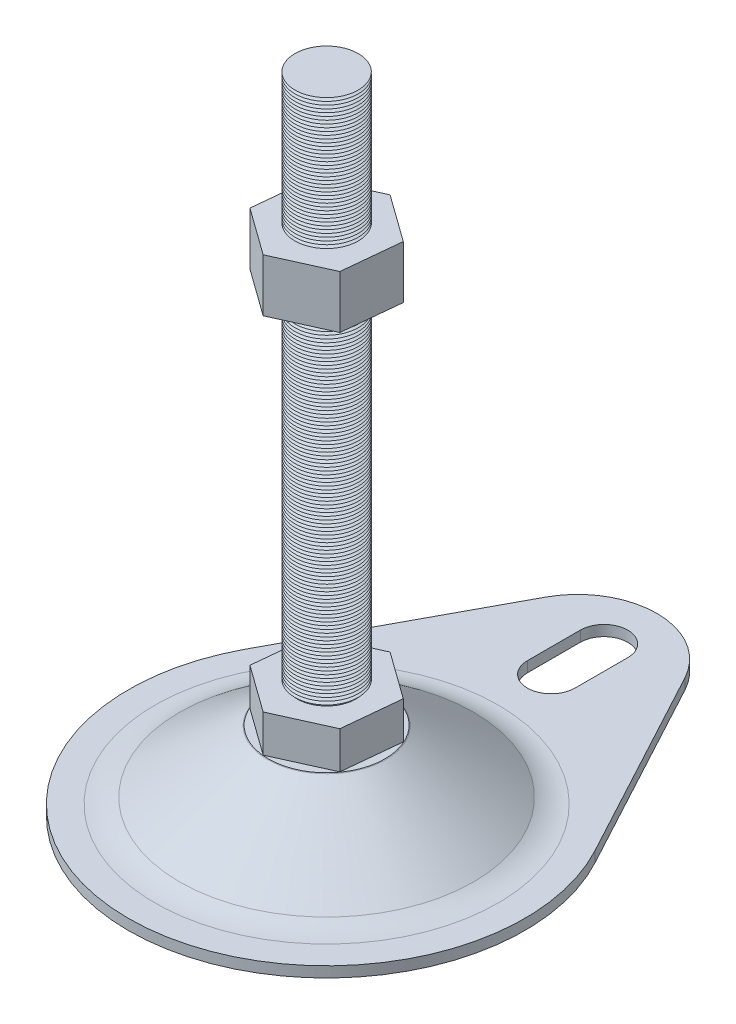
SolidWorks part; units mm, degrees
ref_plane "前视基准面" through (0, 0, 0) normal (0, 0, 1) x (1, 0, 0)
ref_plane "上视基准面" through (0, 0, 0) normal (0, 1, 0) x (1, 0, 0)
ref_plane "右视基准面" through (0, 0, 0) normal (1, 0, 0) x (0, 0, -1)
sketch "草图1" plane through (0, 0, 0) normal (0, 0, 1) x (1, 0, 0)
  line B0 (37.5, -12) -> (37.5, -14)
  line B1 (37.5, -12) -> (32.4605, -12)
  line B2 (27.8204, -10.8583) -> (11.1796, 0.8583)
  line B3 (11.1796, 0.8583) -> (11, 0.9501)
  line B4 (26.8924, -12.63) -> (10.2516, -0.9133)
  line B5 (6.5395, 0) -> (0, 0)
  line B6 (32.4605, -14) -> (37.5, -14)
  line B7 (0, 0) -> (0, 108)
  line B8 (11, 0.9501) -> (11, 8)
  line B9 (5.5767, 8) -> (11, 8)
  line B10 (5.9868, 108) -> (0, 108)
  line B11 (11, 72.9263) -> (11, 82.9263)
  line B12 (5.2185, 82.9263) -> (11, 82.9263)
  line B13 (11, 72.9263) -> (5.5349, 72.9263)
  line B14 (5.5767, 8) -> (5.1, 8.1637)
  line B15 (6, 8.4728) -> (5.1, 8.1637)
  line B16 (6, 8.4728) -> (5.1, 8.7819)
  line B17 (6, 9.091) -> (5.1, 8.7819)
  line B18 (6, 9.091) -> (5.1, 9.4002)
  line B19 (6, 9.7093) -> (5.1, 9.4002)
  line B20 (6, 9.7093) -> (5.1, 10.0184)
  line B21 (6, 10.3275) -> (5.1, 10.0184)
  line B22 (6, 10.3275) -> (5.1, 10.6366)
  line B23 (6, 10.9457) -> (5.1, 10.6366)
  line B24 (6, 10.9457) -> (5.1, 11.2548)
  line B25 (6, 11.5639) -> (5.1, 11.2548)
  line B26 (6, 11.5639) -> (5.1, 11.873)
  line B27 (6, 12.1821) -> (5.1, 11.873)
  line B28 (6, 12.1821) -> (5.1, 12.4912)
  line B29 (6, 12.8003) -> (5.1, 12.4912)
  line B30 (6, 12.8003) -> (5.1, 13.1094)
  line B31 (6, 13.4185) -> (5.1, 13.1094)
  line B32 (6, 13.4185) -> (5.1, 13.7276)
  line B33 (6, 14.0367) -> (5.1, 13.7276)
  line B34 (6, 14.0367) -> (5.1, 14.3458)
  line B35 (6, 14.6549) -> (5.1, 14.3458)
  line B36 (6, 14.6549) -> (5.1, 14.964)
  line B37 (6, 15.2731) -> (5.1, 14.964)
  line B38 (6, 15.2731) -> (5.1, 15.5822)
  line B39 (6, 15.8913) -> (5.1, 15.5822)
  line B40 (6, 15.8913) -> (5.1, 16.2005)
  line B41 (6, 16.5096) -> (5.1, 16.2005)
  line B42 (6, 16.5096) -> (5.1, 16.8187)
  line B43 (6, 17.1278) -> (5.1, 16.8187)
  line B44 (6, 17.1278) -> (5.1, 17.4369)
  line B45 (6, 17.746) -> (5.1, 17.4369)
  line B46 (6, 17.746) -> (5.1, 18.0551)
  line B47 (6, 18.3642) -> (5.1, 18.0551)
  line B48 (6, 18.3642) -> (5.1, 18.6733)
  line B49 (6, 18.9824) -> (5.1, 18.6733)
  line B50 (6, 18.9824) -> (5.1, 19.2915)
  line B51 (6, 19.6006) -> (5.1, 19.2915)
  line B52 (6, 19.6006) -> (5.1, 19.9097)
  line B53 (6, 20.2188) -> (5.1, 19.9097)
  line B54 (6, 20.2188) -> (5.1, 20.5279)
  line B55 (6, 20.837) -> (5.1, 20.5279)
  line B56 (6, 20.837) -> (5.1, 21.1461)
  line B57 (6, 21.4552) -> (5.1, 21.1461)
  line B58 (6, 21.4552) -> (5.1, 21.7643)
  line B59 (6, 22.0734) -> (5.1, 21.7643)
  line B60 (6, 22.0734) -> (5.1, 22.3825)
  line B61 (6, 22.6916) -> (5.1, 22.3825)
  line B62 (6, 22.6916) -> (5.1, 23.0008)
  line B63 (6, 23.3099) -> (5.1, 23.0008)
  line B64 (6, 23.3099) -> (5.1, 23.619)
  line B65 (6, 23.9281) -> (5.1, 23.619)
  line B66 (6, 23.9281) -> (5.1, 24.2372)
  line B67 (6, 24.5463) -> (5.1, 24.2372)
  line B68 (6, 24.5463) -> (5.1, 24.8554)
  line B69 (6, 25.1645) -> (5.1, 24.8554)
  line B70 (6, 25.1645) -> (5.1, 25.4736)
  line B71 (6, 25.7827) -> (5.1, 25.4736)
  line B72 (6, 25.7827) -> (5.1, 26.0918)
  line B73 (6, 26.4009) -> (5.1, 26.0918)
  line B74 (6, 26.4009) -> (5.1, 26.71)
  line B75 (6, 27.0191) -> (5.1, 26.71)
  line B76 (6, 27.0191) -> (5.1, 27.3282)
  line B77 (6, 27.6373) -> (5.1, 27.3282)
  line B78 (6, 27.6373) -> (5.1, 27.9464)
  line B79 (6, 28.2555) -> (5.1, 27.9464)
  line B80 (6, 28.2555) -> (5.1, 28.5646)
  line B81 (6, 28.8737) -> (5.1, 28.5646)
  line B82 (6, 28.8737) -> (5.1, 29.1828)
  line B83 (6, 29.492) -> (5.1, 29.1828)
  line B84 (6, 29.492) -> (5.1, 29.8011)
  line B85 (6, 30.1102) -> (5.1, 29.8011)
  line B86 (6, 30.1102) -> (5.1, 30.4193)
  line B87 (6, 30.7284) -> (5.1, 30.4193)
  line B88 (6, 30.7284) -> (5.1, 31.0375)
  line B89 (6, 31.3466) -> (5.1, 31.0375)
  line B90 (6, 31.3466) -> (5.1, 31.6557)
  line B91 (6, 31.9648) -> (5.1, 31.6557)
  line B92 (6, 31.9648) -> (5.1, 32.2739)
  line B93 (6, 32.583) -> (5.1, 32.2739)
  line B94 (6, 32.583) -> (5.1, 32.8921)
  line B95 (6, 33.2012) -> (5.1, 32.8921)
  line B96 (6, 33.2012) -> (5.1, 33.5103)
  line B97 (6, 33.8194) -> (5.1, 33.5103)
  line B98 (6, 33.8194) -> (5.1, 34.1285)
  line B99 (6, 34.4376) -> (5.1, 34.1285)
  line B100 (6, 34.4376) -> (5.1, 34.7467)
  line B101 (6, 35.0558) -> (5.1, 34.7467)
  line B102 (6, 35.0558) -> (5.1, 35.3649)
  line B103 (6, 35.674) -> (5.1, 35.3649)
  line B104 (6, 35.674) -> (5.1, 35.9831)
  line B105 (6, 36.2923) -> (5.1, 35.9831)
  line B106 (6, 36.2923) -> (5.1, 36.6014)
  line B107 (6, 36.9105) -> (5.1, 36.6014)
  line B108 (6, 36.9105) -> (5.1, 37.2196)
  line B109 (6, 37.5287) -> (5.1, 37.2196)
  line B110 (6, 37.5287) -> (5.1, 37.8378)
  line B111 (6, 38.1469) -> (5.1, 37.8378)
  line B112 (6, 38.1469) -> (5.1, 38.456)
  line B113 (6, 38.7651) -> (5.1, 38.456)
  line B114 (6, 38.7651) -> (5.1, 39.0742)
  line B115 (6, 39.3833) -> (5.1, 39.0742)
  line B116 (6, 39.3833) -> (5.1, 39.6924)
  line B117 (6, 40.0015) -> (5.1, 39.6924)
  line B118 (6, 40.0015) -> (5.1, 40.3106)
  line B119 (6, 40.6197) -> (5.1, 40.3106)
  line B120 (6, 40.6197) -> (5.1, 40.9288)
  line B121 (6, 41.2379) -> (5.1, 40.9288)
  line B122 (6, 41.2379) -> (5.1, 41.547)
  line B123 (6, 41.8561) -> (5.1, 41.547)
  line B124 (6, 41.8561) -> (5.1, 42.1652)
  line B125 (6, 42.4743) -> (5.1, 42.1652)
  line B126 (6, 42.4743) -> (5.1, 42.7834)
  line B127 (6, 43.0926) -> (5.1, 42.7834)
  line B128 (6, 43.0926) -> (5.1, 43.4017)
  line B129 (6, 43.7108) -> (5.1, 43.4017)
  line B130 (6, 43.7108) -> (5.1, 44.0199)
  line B131 (6, 44.329) -> (5.1, 44.0199)
  line B132 (6, 44.329) -> (5.1, 44.6381)
  line B133 (6, 44.9472) -> (5.1, 44.6381)
  line B134 (6, 44.9472) -> (5.1, 45.2563)
  line B135 (6, 45.5654) -> (5.1, 45.2563)
  line B136 (6, 45.5654) -> (5.1, 45.8745)
  line B137 (6, 46.1836) -> (5.1, 45.8745)
  line B138 (6, 46.1836) -> (5.1, 46.4927)
  line B139 (6, 46.8018) -> (5.1, 46.4927)
  line B140 (6, 46.8018) -> (5.1, 47.1109)
  line B141 (6, 47.42) -> (5.1, 47.1109)
  line B142 (6, 47.42) -> (5.1, 47.7291)
  line B143 (6, 48.0382) -> (5.1, 47.7291)
  line B144 (6, 48.0382) -> (5.1, 48.3473)
  line B145 (6, 48.6564) -> (5.1, 48.3473)
  line B146 (6, 48.6564) -> (5.1, 48.9655)
  line B147 (6, 49.2746) -> (5.1, 48.9655)
  line B148 (6, 49.2746) -> (5.1, 49.5838)
  line B149 (6, 49.8929) -> (5.1, 49.5838)
  line B150 (6, 49.8929) -> (5.1, 50.202)
  line B151 (6, 50.5111) -> (5.1, 50.202)
  line B152 (6, 50.5111) -> (5.1, 50.8202)
  line B153 (6, 51.1293) -> (5.1, 50.8202)
  line B154 (6, 51.1293) -> (5.1, 51.4384)
  line B155 (6, 51.7475) -> (5.1, 51.4384)
  line B156 (6, 51.7475) -> (5.1, 52.0566)
  line B157 (6, 52.3657) -> (5.1, 52.0566)
  line B158 (6, 52.3657) -> (5.1, 52.6748)
  line B159 (6, 52.9839) -> (5.1, 52.6748)
  line B160 (6, 52.9839) -> (5.1, 53.293)
  line B161 (6, 53.6021) -> (5.1, 53.293)
  line B162 (6, 53.6021) -> (5.1, 53.9112)
  line B163 (6, 54.2203) -> (5.1, 53.9112)
  line B164 (6, 54.2203) -> (5.1, 54.5294)
  line B165 (6, 54.8385) -> (5.1, 54.5294)
  line B166 (6, 54.8385) -> (5.1, 55.1476)
  line B167 (6, 55.4567) -> (5.1, 55.1476)
  line B168 (6, 55.4567) -> (5.1, 55.7658)
  line B169 (6, 56.0749) -> (5.1, 55.7658)
  line B170 (6, 56.0749) -> (5.1, 56.3841)
  line B171 (6, 56.6932) -> (5.1, 56.3841)
  line B172 (6, 56.6932) -> (5.1, 57.0023)
  line B173 (6, 57.3114) -> (5.1, 57.0023)
  line B174 (6, 57.3114) -> (5.1, 57.6205)
  line B175 (6, 57.9296) -> (5.1, 57.6205)
  line B176 (6, 57.9296) -> (5.1, 58.2387)
  line B177 (6, 58.5478) -> (5.1, 58.2387)
  line B178 (6, 58.5478) -> (5.1, 58.8569)
  line B179 (6, 59.166) -> (5.1, 58.8569)
  line B180 (6, 59.166) -> (5.1, 59.4751)
  line B181 (6, 59.7842) -> (5.1, 59.4751)
  line B182 (6, 59.7842) -> (5.1, 60.0933)
  line B183 (6, 60.4024) -> (5.1, 60.0933)
  line B184 (6, 60.4024) -> (5.1, 60.7115)
  line B185 (6, 61.0206) -> (5.1, 60.7115)
  line B186 (6, 61.0206) -> (5.1, 61.3297)
  line B187 (6, 61.6388) -> (5.1, 61.3297)
  line B188 (6, 61.6388) -> (5.1, 61.9479)
  line B189 (6, 62.257) -> (5.1, 61.9479)
  line B190 (6, 62.257) -> (5.1, 62.5661)
  line B191 (6, 62.8752) -> (5.1, 62.5661)
  line B192 (6, 62.8752) -> (5.1, 63.1844)
  line B193 (6, 63.4935) -> (5.1, 63.1844)
  line B194 (6, 63.4935) -> (5.1, 63.8026)
  line B195 (6, 64.1117) -> (5.1, 63.8026)
  line B196 (6, 64.1117) -> (5.1, 64.4208)
  line B197 (6, 64.7299) -> (5.1, 64.4208)
  line B198 (6, 64.7299) -> (5.1, 65.039)
  line B199 (6, 65.3481) -> (5.1, 65.039)
  line B200 (6, 65.3481) -> (5.1, 65.6572)
  line B201 (6, 65.9663) -> (5.1, 65.6572)
  line B202 (6, 65.9663) -> (5.1, 66.2754)
  line B203 (6, 66.5845) -> (5.1, 66.2754)
  line B204 (6, 66.5845) -> (5.1, 66.8936)
  line B205 (6, 67.2027) -> (5.1, 66.8936)
  line B206 (6, 67.2027) -> (5.1, 67.5118)
  line B207 (6, 67.8209) -> (5.1, 67.5118)
  line B208 (6, 67.8209) -> (5.1, 68.13)
  line B209 (6, 68.4391) -> (5.1, 68.13)
  line B210 (6, 68.4391) -> (5.1, 68.7482)
  line B211 (6, 69.0573) -> (5.1, 68.7482)
  line B212 (6, 69.0573) -> (5.1, 69.3664)
  line B213 (6, 69.6756) -> (5.1, 69.3664)
  line B214 (6, 69.6756) -> (5.1, 69.9847)
  line B215 (6, 70.2938) -> (5.1, 69.9847)
  line B216 (6, 70.2938) -> (5.1, 70.6029)
  line B217 (6, 70.912) -> (5.1, 70.6029)
  line B218 (6, 70.912) -> (5.1, 71.2211)
  line B219 (6, 71.5302) -> (5.1, 71.2211)
  line B220 (6, 71.5302) -> (5.1, 71.8393)
  line B221 (6, 72.1484) -> (5.1, 71.8393)
  line B222 (6, 72.1484) -> (5.1, 72.4575)
  line B223 (6, 72.7666) -> (5.1, 72.4575)
  line B224 (6, 72.7666) -> (5.5349, 72.9263)
  line B225 (5.2185, 82.9263) -> (5.1, 82.967)
  line B226 (6, 83.2762) -> (5.1, 82.967)
  line B227 (6, 83.2762) -> (5.1, 83.5853)
  line B228 (6, 83.8944) -> (5.1, 83.5853)
  line B229 (6, 83.8944) -> (5.1, 84.2035)
  line B230 (6, 84.5126) -> (5.1, 84.2035)
  line B231 (6, 84.5126) -> (5.1, 84.8217)
  line B232 (6, 85.1308) -> (5.1, 84.8217)
  line B233 (6, 85.1308) -> (5.1, 85.4399)
  line B234 (6, 85.749) -> (5.1, 85.4399)
  line B235 (6, 85.749) -> (5.1, 86.0581)
  line B236 (6, 86.3672) -> (5.1, 86.0581)
  line B237 (6, 86.3672) -> (5.1, 86.6763)
  line B238 (6, 86.9854) -> (5.1, 86.6763)
  line B239 (6, 86.9854) -> (5.1, 87.2945)
  line B240 (6, 87.6036) -> (5.1, 87.2945)
  line B241 (6, 87.6036) -> (5.1, 87.9127)
  line B242 (6, 88.2218) -> (5.1, 87.9127)
  line B243 (6, 88.2218) -> (5.1, 88.5309)
  line B244 (6, 88.84) -> (5.1, 88.5309)
  line B245 (6, 88.84) -> (5.1, 89.1491)
  line B246 (6, 89.4582) -> (5.1, 89.1491)
  line B247 (6, 89.4582) -> (5.1, 89.7674)
  line B248 (6, 90.0765) -> (5.1, 89.7674)
  line B249 (6, 90.0765) -> (5.1, 90.3856)
  line B250 (6, 90.6947) -> (5.1, 90.3856)
  line B251 (6, 90.6947) -> (5.1, 91.0038)
  line B252 (6, 91.3129) -> (5.1, 91.0038)
  line B253 (6, 91.3129) -> (5.1, 91.622)
  line B254 (6, 91.9311) -> (5.1, 91.622)
  line B255 (6, 91.9311) -> (5.1, 92.2402)
  line B256 (6, 92.5493) -> (5.1, 92.2402)
  line B257 (6, 92.5493) -> (5.1, 92.8584)
  line B258 (6, 93.1675) -> (5.1, 92.8584)
  line B259 (6, 93.1675) -> (5.1, 93.4766)
  line B260 (6, 93.7857) -> (5.1, 93.4766)
  line B261 (6, 93.7857) -> (5.1, 94.0948)
  line B262 (6, 94.4039) -> (5.1, 94.0948)
  line B263 (6, 94.4039) -> (5.1, 94.713)
  line B264 (6, 95.0221) -> (5.1, 94.713)
  line B265 (6, 95.0221) -> (5.1, 95.3312)
  line B266 (6, 95.6403) -> (5.1, 95.3312)
  line B267 (6, 95.6403) -> (5.1, 95.9494)
  line B268 (6, 96.2585) -> (5.1, 95.9494)
  line B269 (6, 96.2585) -> (5.1, 96.5677)
  line B270 (6, 96.8768) -> (5.1, 96.5677)
  line B271 (6, 96.8768) -> (5.1, 97.1859)
  line B272 (6, 97.495) -> (5.1, 97.1859)
  line B273 (6, 97.495) -> (5.1, 97.8041)
  line B274 (6, 98.1132) -> (5.1, 97.8041)
  line B275 (6, 98.1132) -> (5.1, 98.4223)
  line B276 (6, 98.7314) -> (5.1, 98.4223)
  line B277 (6, 98.7314) -> (5.1, 99.0405)
  line B278 (6, 99.3496) -> (5.1, 99.0405)
  line B279 (6, 99.3496) -> (5.1, 99.6587)
  line B280 (6, 99.9678) -> (5.1, 99.6587)
  line B281 (6, 99.9678) -> (5.1, 100.2769)
  line B282 (6, 100.586) -> (5.1, 100.2769)
  line B283 (6, 100.586) -> (5.1, 100.8951)
  line B284 (6, 101.2042) -> (5.1, 100.8951)
  line B285 (6, 101.2042) -> (5.1, 101.5133)
  line B286 (6, 101.8224) -> (5.1, 101.5133)
  line B287 (6, 101.8224) -> (5.1, 102.1315)
  line B288 (6, 102.4406) -> (5.1, 102.1315)
  line B289 (6, 102.4406) -> (5.1, 102.7497)
  line B290 (6, 103.0588) -> (5.1, 102.7497)
  line B291 (6, 103.0588) -> (5.1, 103.368)
  line B292 (6, 103.6771) -> (5.1, 103.368)
  line B293 (6, 103.6771) -> (5.1, 103.9862)
  line B294 (6, 104.2953) -> (5.1, 103.9862)
  line B295 (6, 104.2953) -> (5.1, 104.6044)
  line B296 (6, 104.9135) -> (5.1, 104.6044)
  line B297 (6, 104.9135) -> (5.1, 105.2226)
  line B298 (6, 105.5317) -> (5.1, 105.2226)
  line B299 (6, 105.5317) -> (5.1, 105.8408)
  line B300 (6, 106.1499) -> (5.1, 105.8408)
  line B301 (6, 106.1499) -> (5.1, 106.459)
  line B302 (6, 106.7681) -> (5.1, 106.459)
  line B303 (6, 106.7681) -> (5.1, 107.0772)
  line B304 (6, 107.3863) -> (5.1, 107.0772)
  line B305 (6, 107.3863) -> (5.1, 107.6954)
  line B306 (5.9868, 108) -> (5.1, 107.6954)
  arc B307 (27.8204, -10.8583) -> (32.4605, -12) centre (32.4605, -2) ccw
  arc B308 (26.8924, -12.63) -> (32.4605, -14) centre (32.4605, -2) ccw
  arc B309 (10.2516, -0.9133) -> (6.5395, 0) centre (6.5395, -8) ccw
sketch_block_instance "A$C43B54E7A-1"
sketch_block "A$C43B54E7A"
revolve "旋转1" add sketch "草图1" angle 360 about L7
sketch "草图3" plane through (0, 82.9263, 0) normal (0, 1, 0) x (1, 0, 0)
  line L1 (9.9992, 4.5109) -> (1.0931, 10.9151)
  line L2 (1.0931, 10.9151) -> (-8.9062, 6.4041)
  line L3 (-8.9062, 6.4041) -> (-9.9992, -4.5109)
  line L4 (-9.9992, -4.5109) -> (-1.0931, -10.9151)
  line L5 (-1.0931, -10.9151) -> (8.9062, -6.4041)
  line L6 (8.9062, -6.4041) -> (9.9992, 4.5109)
  line L7 (-31.8659, 36.4786) -> (28.1136, 36.4786)
  line L8 (-31.8659, 36.4786) -> (-31.8659, -23.6177)
  line L9 (-31.8659, -23.6177) -> (28.1136, -23.6177)
  line L10 (28.1136, 36.4786) -> (28.1136, -23.6177)
  circle A0 centre (0, 0) radius 9.5 construction
extrude "切除-拉伸1" cut sketch "草图3" against normal blind 82
sketch "草图4" plane through (0, -12, 0) normal (0, 1, 0) x (1, 0, 0)
  line L0 (13.2104, 54.6053) -> (33.0261, 17.7632)
  line L2 (-13.2104, 54.6053) -> (-33.0261, 17.7632)
  line L3 (0, 47.5) -> (0, 16.1743) construction
  arc A0 (13.2104, 54.6053) -> (-13.2104, 54.6053) centre (0, 47.5) ccw
  circle A1 centre (0, 0) radius 5.9868 construction
  circle A2 centre (0, 0) radius 37.5 construction
  arc A3 (33.0261, 17.7632) -> (-33.0261, 17.7632) centre (0, 0) ccw
  dimension "D1" = 47.5
extrude "凸台-拉伸1" add sketch "草图4" against normal up to surface (2 mm away) up to face at (0, -14, -37.5)
sketch "草图5" plane through (0, -12, 0) normal (0, 1, 0) x (1, 0, 0)
  line L0 (0, 42.5) -> (0, 52.5) construction
  line L1 (-4.5, 42.5) -> (-4.5, 52.5)
  line L2 (4.5, 42.5) -> (4.5, 52.5)
  arc A0 (-4.5, 42.5) -> (4.5, 42.5) centre (0, 42.5) ccw
  arc A1 (4.5, 52.5) -> (-4.5, 52.5) centre (0, 52.5) ccw
  point P3 (0, 47.5)
  dimension "D1" = 47.5
  dimension "D2" = 10
  dimension "D3" = 9
extrude "切除-拉伸2" cut sketch "草图5" against normal through all
